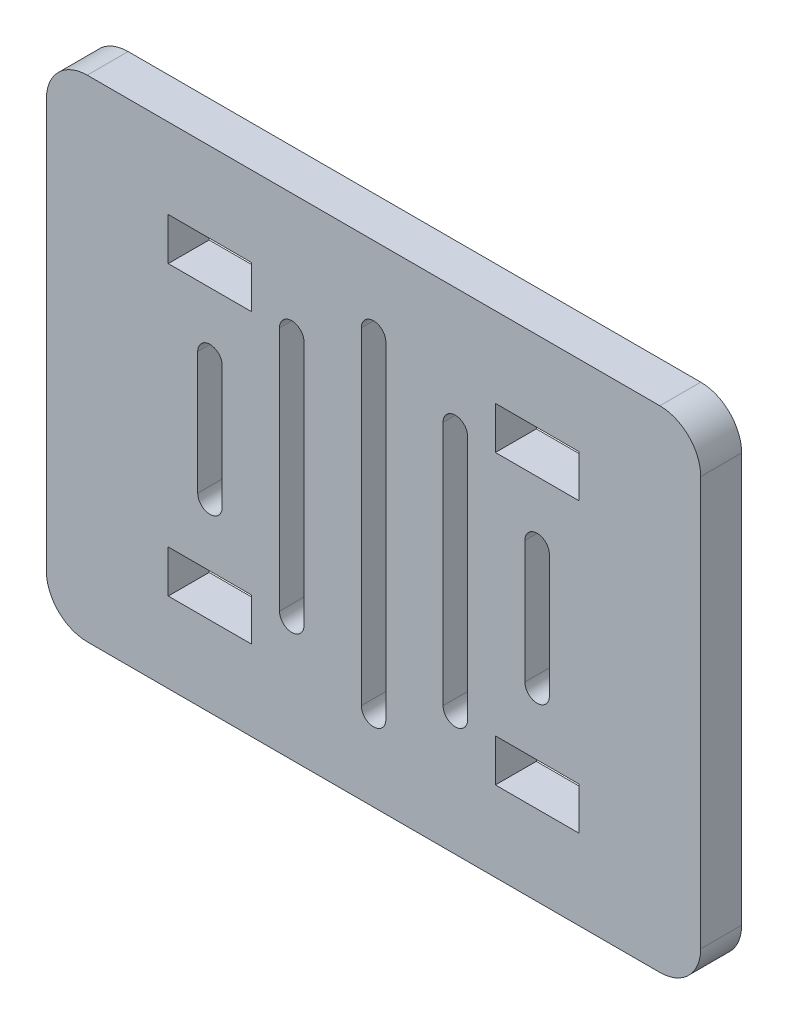
SolidWorks part; units mm, degrees
material "AISI 1020 Steel, Cold Rolled"
ref_plane "Front Plane" through (0, 0, 0) normal (1, 0, 0) x (0, 1, 0)
ref_plane "Top Plane" through (0, 0, 0) normal (0, 0, 1) x (0, 1, 0)
ref_plane "Right Plane" through (0, 0, 0) normal (0, 1, 0) x (-1, 0, 0)
sketch "Sketch1" plane through (0, 0, 0) normal (0, 0, 1) x (0, 1, 0)
  line L0 (0, 0) -> (0, 40) construction
  line L1 (0, -0.75) -> (0, 0)
  line L2 (-15, 0) -> (15, 0) construction
  line L3 (15, -5.1) -> (15, 5.1)
  line L4 (20.2, -5.1) -> (20.2, 5.1)
  line L5 (15, -5.1) -> (20.2, -5.1)
  line L6 (15, 5.1) -> (20.2, 5.1)
  line L7 (0, 20) -> (15, 20) construction
  line L8 (20.2, 45.1) -> (20.2, 34.9)
  line L9 (15, 45.1) -> (20.2, 45.1)
  line L10 (15, 45.1) -> (15, 34.9)
  line L11 (15, 34.9) -> (20.2, 34.9)
  line L12 (-15, 40) -> (15, 40) construction
  line L13 (-15, 5.1) -> (-20.2, 5.1)
  line L14 (-15, -5.1) -> (-20.2, -5.1)
  line L15 (-20.2, -5.1) -> (-20.2, 5.1)
  line L16 (-15, -5.1) -> (-15, 5.1)
  line L17 (-15, 34.9) -> (-20.2, 34.9)
  line L18 (-15, 45.1) -> (-15, 34.9)
  line L19 (-15, 45.1) -> (-20.2, 45.1)
  line L20 (-20.2, 45.1) -> (-20.2, 34.9)
  line L21 (0, 40) -> (0, 60) construction
  line L22 (0, 0) -> (0, -20)
  line L23 (30, 0) -> (30, -20)
  line L24 (30, 0) -> (30, 40)
  line L25 (30, 40) -> (30, 60)
  line L26 (-30, 0) -> (-30, -20)
  line L27 (-30, 0) -> (-30, 40)
  line L28 (-30, 40) -> (-30, 60)
  line L29 (30, -20) -> (-30, -20)
  line L30 (30, 60) -> (-30, 60)
  line L31 (7.5, 40) -> (-7.5, 40)
  line L32 (0, 40) -> (0, 30)
  line L33 (15, 30) -> (-15, 30)
  line L34 (0, 30) -> (0, 20)
  line L35 (20, 20) -> (-20, 20)
  line L36 (7.5, 0) -> (-7.5, 0)
  line L37 (15, 10) -> (-15, 10)
  line L38 (7.5, 41.5) -> (-7.5, 41.5)
  line L39 (15, 31.5) -> (-15, 31.5)
  line L40 (20, 21.5) -> (-20, 21.5)
  line L41 (15, 11.5) -> (-15, 11.5)
  line L42 (7.5, 1.5) -> (-7.5, 1.5)
  line L43 (7.5, 38.5) -> (-7.5, 38.5)
  line L44 (15, 28.5) -> (-15, 28.5)
  line L45 (20, 18.5) -> (-20, 18.5)
  line L46 (15, 8.5) -> (-15, 8.5)
  line L47 (7.5, -1.5) -> (-7.5, -1.5)
  arc A0 (7.5, 41.5) -> (7.5, 38.5) centre (7.5, 40) cw
  arc A1 (-7.5, 41.5) -> (-7.5, 38.5) centre (-7.5, 40) ccw
  arc A2 (15, 31.5) -> (15, 28.5) centre (15, 30) cw
  arc A3 (-15, 31.5) -> (-15, 28.5) centre (-15, 30) ccw
  arc A4 (20, 21.5) -> (20, 18.5) centre (20, 20) cw
  arc A5 (-20, 21.5) -> (-20, 18.5) centre (-20, 20) ccw
  arc A6 (15, 11.5) -> (15, 8.5) centre (15, 10) cw
  arc A7 (-15, 11.5) -> (-15, 8.5) centre (-15, 10) ccw
  arc A8 (7.5, 1.5) -> (7.5, -1.5) centre (7.5, 0) cw
  arc A9 (-7.5, 1.5) -> (-7.5, -1.5) centre (-7.5, 0) ccw
  point P4 (0, 0)
  point P10 (15, 0)
  point P19 (-15, 0)
  point P42 (0, 40)
  point P46 (0, 30)
  point P49 (0, 20)
  dimension "D1" = 15
  dimension "D2" = 10.2
  dimension "D3" = 40
  dimension "D4" = 5.2
  dimension "D5" = 20
  dimension "D6" = 20
  dimension "D7" = 15
  dimension "D8" = 10
  dimension "D9" = 30
  dimension "D10" = 40
  dimension "D11" = 30
  dimension "D12" = 30
extrude "Boss-Extrude1" add sketch "Sketch1" along normal mid plane 5
fillet "Fillet1" radius 5 4 edges at (-60, -30, 0) (-60, 30, 0) (20, 30, 0) (20, -30, 0)
